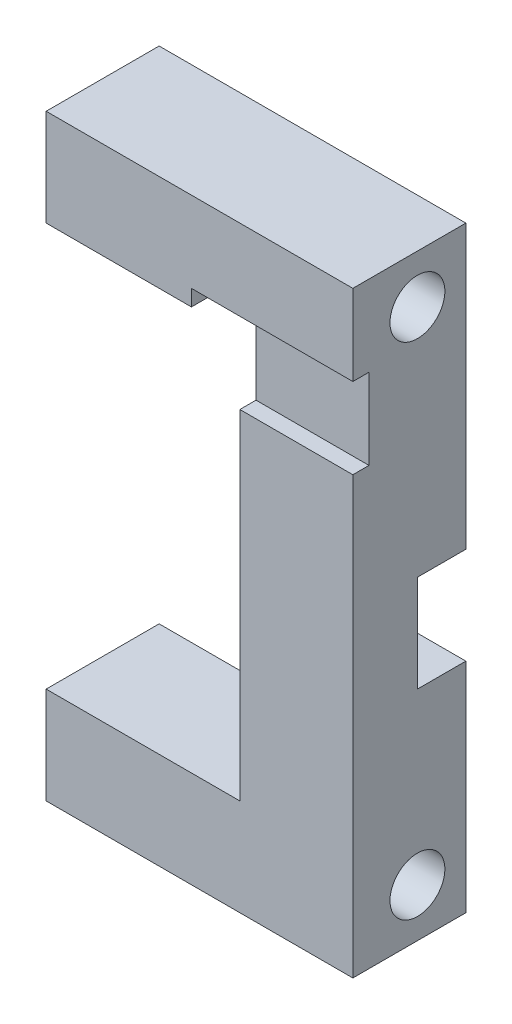
SolidWorks part; units mm, degrees
ref_plane "前视基准面" through (0, 0, 0) normal (0, 0, 1) x (1, 0, 0)
ref_plane "上视基准面" through (0, 0, 0) normal (0, 1, 0) x (1, 0, 0)
ref_plane "右视基准面" through (0, 0, 0) normal (1, 0, 0) x (0, 0, -1)
other "Configuration Table"
sketch "草图1" plane through (0, 0, 0) normal (0, 0, 1) x (1, 0, 0)
  line L0 (0, 0) -> (0, 6)
  line L9 (0, 6) -> (12, 6)
  line L10 (12, 11) -> (12, 26)
  line L11 (12, 31) -> (0, 31)
  line L12 (0, 31) -> (0, 37)
  line L13 (0, 37) -> (19, 37)
  line L14 (19, 37) -> (19, 0)
  line L15 (19, 0) -> (0, 0)
  line L16 (12, 31) -> (12, 26)
  line L18 (12, 6) -> (12, 11)
  dimension "D1" = 7
  dimension "D2" = 25
  dimension "D3" = 6
  dimension "D4" = 6
  dimension "D5" = 19
  dimension "D6" = 5
  dimension "D7" = 5
extrude "凸台-拉伸1" add sketch "草图1" along normal blind 7
sketch "草图2" plane through (0, 0, 0) normal (0, 0, -1) x (-1, 0, 0)
  line L0 (-19, 0) -> (-19, 37) construction
  line L1 (-19, 19.5) -> (-12, 19.5)
  line L2 (-19, 19.5) -> (-19, 13.5)
  line L3 (-19, 13.5) -> (-12, 13.5)
  line L4 (-12, 19.5) -> (-12, 13.5)
  line L5 (0, 31) -> (-12, 31) construction
  dimension "D1" = 7
  dimension "D2" = 6
  dimension "D3" = 11.5
extrude "切除-拉伸1" cut sketch "草图2" against normal blind 3
sketch "草图3" plane through (0, 0, 0) normal (-1, 0, 0) x (0, 0, 1)
  line L0 (7, 37) -> (7, 31) construction
  line L1 (7, 6) -> (7, 0) construction
  line L3 (0, 37) -> (0, 31) construction
  circle A0 centre (3, 34) radius 1.7
  circle A1 centre (3, 3) radius 1.7
  point P7 (7, 34)
  point P10 (7, 3)
  dimension "D1" = 3.4
  dimension "D2" = 3
extrude "切除-拉伸2" cut sketch "草图3" against normal through all
sketch "草图4" plane through (0, 0, 7) normal (0, 0, 1) x (1, 0, 0)
  line L0 (19, 0) -> (19, 37) construction
  line L1 (9, 32) -> (19, 32)
  line L2 (9, 32) -> (9, 27)
  line L3 (9, 27) -> (19, 27)
  line L4 (19, 32) -> (19, 27)
  line L5 (0, 31) -> (12, 31) construction
  dimension "D1" = 10
  dimension "D2" = 5
  dimension "D3" = 1
extrude "切除-拉伸3" cut sketch "草图4" against normal blind 1
